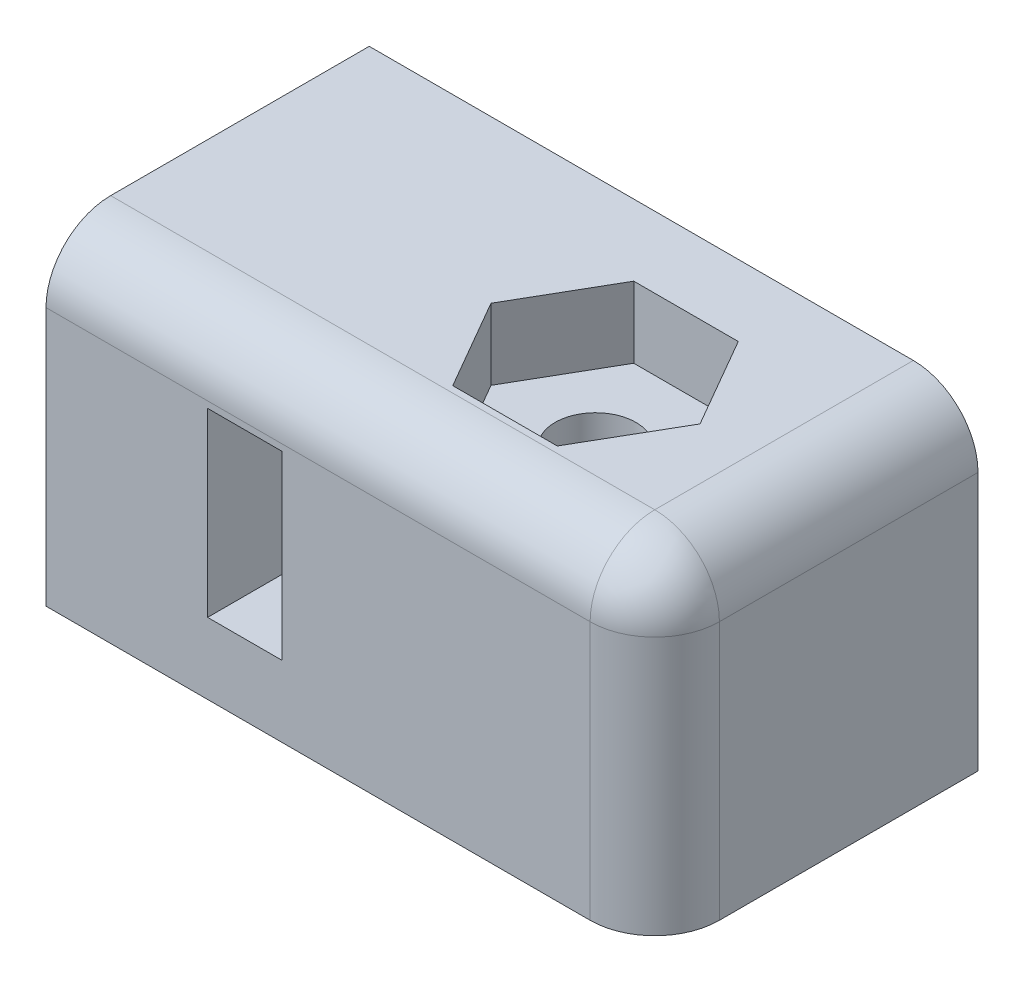
SolidWorks part; units mm, degrees
ref_plane "Front Plane" through (0, 0, 0) normal (0, 0, 1) x (1, 0, 0)
ref_plane "Top Plane" through (0, 0, 0) normal (0, 1, 0) x (1, 0, 0)
ref_plane "Right Plane" through (0, 0, 0) normal (1, 0, 0) x (0, 0, -1)
sketch "Sketch1" plane through (0, 0, 0) normal (0, 1, 0) x (1, 0, 0)
  line L1 (0, 0) -> (74.5, 0)
  line L2 (0, 0) -> (0, 10)
  line L3 (0, 10) -> (74.5, 10)
  line L4 (74.5, 0) -> (74.5, 10)
  dimension "D1" = 74.5
  dimension "D2" = 10
extrude "Boss-Extrude1" add sketch "Sketch1" along normal blind 10
sketch "Sketch2" plane through (0, 10, 0) normal (0, 1, 0) x (1, 0, 0)
  line L0 (0, 5) -> (74.5, 5) construction
  line L1 (0, 10) -> (0, 0) construction
  line L2 (74.5, 0) -> (74.5, 10) construction
  circle A0 centre (12, 5) radius 1.25
  circle A1 centre (62.5, 5) radius 1.25
  dimension "D3" = 2.5
  dimension "D4" = 2.5
  dimension "D1" = 12
  dimension "D2" = 12
extrude "Cut-Extrude1" cut sketch "Sketch2" against normal blind 10
sketch "Sketch4" plane through (74.5, 0, 0) normal (1, 0, 0) x (0, 0, -1)
  line L0 (5, 10) -> (5, 4.1725) construction
  line L1 (0, 10) -> (10, 10) construction
  line L2 (0, 5) -> (5.9702, 5) construction
  line L3 (0, 10) -> (0, 0) construction
  circle A0 centre (5, 5) radius 1.25
  dimension "D1" = 2.5
extrude "Cut-Extrude3" cut sketch "Sketch4" against normal blind 5
sketch "Sketch5" plane through (0, 0, 0) normal (-1, 0, 0) x (0, 0, 1)
  line L0 (-5, 10) -> (-5, 0) construction
  line L1 (-10, 10) -> (0, 10) construction
  line L2 (-10, 0) -> (0, 0) construction
  line L3 (-10, 5) -> (0, 5) construction
  line L4 (-10, 10) -> (-10, 0) construction
  line L5 (0, 10) -> (0, 0) construction
  circle A0 centre (-5, 5) radius 1.25
  dimension "D1" = 2.5
extrude "Cut-Extrude4" cut sketch "Sketch5" against normal blind 12
sketch "Sketch6" plane through (0, 10, 0) normal (0, 1, 0) x (1, 0, 0)
  line L0 (74.5, 10) -> (0, 10) construction
  line L1 (13.6166, 2.2) -> (15.2332, 5)
  line L2 (15.2332, 5) -> (13.6166, 7.8)
  line L3 (13.6166, 7.8) -> (10.3834, 7.8)
  line L4 (10.3834, 7.8) -> (8.7668, 5)
  line L5 (8.7668, 5) -> (10.3834, 2.2)
  line L6 (10.3834, 2.2) -> (13.6166, 2.2)
  circle A0 centre (12, 5) radius 2.8 construction
  dimension "D1" = 5.6
extrude "Cut-Extrude5" cut sketch "Sketch6" against normal blind 2.2
sketch "Sketch7" plane through (0, 10, 0) normal (0, 1, 0) x (1, 0, 0)
  line L0 (74.5, 10) -> (0, 10) construction
  line L1 (60.8834, 7.8) -> (59.2668, 5)
  line L2 (59.2668, 5) -> (60.8834, 2.2)
  line L3 (60.8834, 2.2) -> (64.1166, 2.2)
  line L4 (64.1166, 2.2) -> (65.7332, 5)
  line L5 (65.7332, 5) -> (64.1166, 7.8)
  line L6 (64.1166, 7.8) -> (60.8834, 7.8)
  circle A0 centre (62.5, 5) radius 2.8 construction
  dimension "D1" = 5.6
extrude "Cut-Extrude6" cut sketch "Sketch7" against normal blind 2.2
sketch "Sketch11" plane through (0, 0, 0) normal (0, 0, 1) x (1, 0, 0)
  line L0 (0, 5) -> (74.5, 5) construction
  line L1 (0, 10) -> (0, 0) construction
  line L2 (74.5, 10) -> (74.5, 0) construction
  line L4 (5, 2.2) -> (7.3, 2.2)
  line L5 (5, 2.2) -> (5, 7.8)
  line L6 (5, 7.8) -> (7.3, 7.8)
  line L7 (7.3, 2.2) -> (7.3, 7.8)
  line L8 (5, 2.2) -> (7.3, 7.8) construction
  line L9 (5, 7.8) -> (7.3, 2.2) construction
  line L10 (67.2, 2.2) -> (69.5, 2.2)
  line L11 (67.2, 2.2) -> (67.2, 7.8)
  line L12 (67.2, 7.8) -> (69.5, 7.8)
  line L13 (69.5, 2.2) -> (69.5, 7.8)
  line L14 (67.2, 2.2) -> (69.5, 7.8) construction
  line L15 (67.2, 7.8) -> (69.5, 2.2) construction
  point P6 (6.15, 5)
  point P11 (68.35, 5)
  dimension "D1" = 2.3
  dimension "D2" = 5.6
  dimension "D3" = 2.3
  dimension "D4" = 5.6
  dimension "D5" = 5
  dimension "D6" = 5
extrude "Cut-Extrude9" cut sketch "Sketch11" against normal blind 7.3
sketch "Sketch12" plane through (0, 0, 0) normal (0, 0, 1) x (1, 0, 0)
  line L1 (118.9376, 29.7047) -> (26.1416, 29.7047)
  line L2 (118.9376, 29.7047) -> (118.9376, -5.4838)
  line L3 (118.9376, -5.4838) -> (26.1416, -5.4838)
  line L4 (26.1416, 29.7047) -> (26.1416, -5.4838)
  line L5 (118.9376, 29.7047) -> (26.1416, -5.4838) construction
  line L6 (118.9376, -5.4838) -> (26.1416, 29.7047) construction
  point P0 (72.5396, 12.1105)
extrude "Cut-Extrude10" cut sketch "Sketch12" against normal blind 14
sketch "Sketch13" plane through (0, 10, 0) normal (0, 1, 0) x (1, 0, 0)
  line L1 (18.8331, 11.2154) -> (26.9421, 11.2154)
  line L2 (18.8331, 11.2154) -> (18.8331, -1.0992)
  line L3 (18.8331, -1.0992) -> (26.9421, -1.0992)
  line L4 (26.9421, 11.2154) -> (26.9421, -1.0992)
  line L5 (18.8331, 11.2154) -> (26.9421, -1.0992) construction
  line L6 (18.8331, -1.0992) -> (26.9421, 11.2154) construction
  point P0 (22.8876, 5.0581)
extrude "Cut-Extrude11" cut sketch "Sketch13" against normal blind 12
fillet "Fillet2" radius 2 1 edges at (18.8331, 5, 0)
fillet "Fillet3" radius 2 3 edges at (8.4165, 10, 0) (18.2473, 10, -0.5858) (18.8331, 10, -6)
